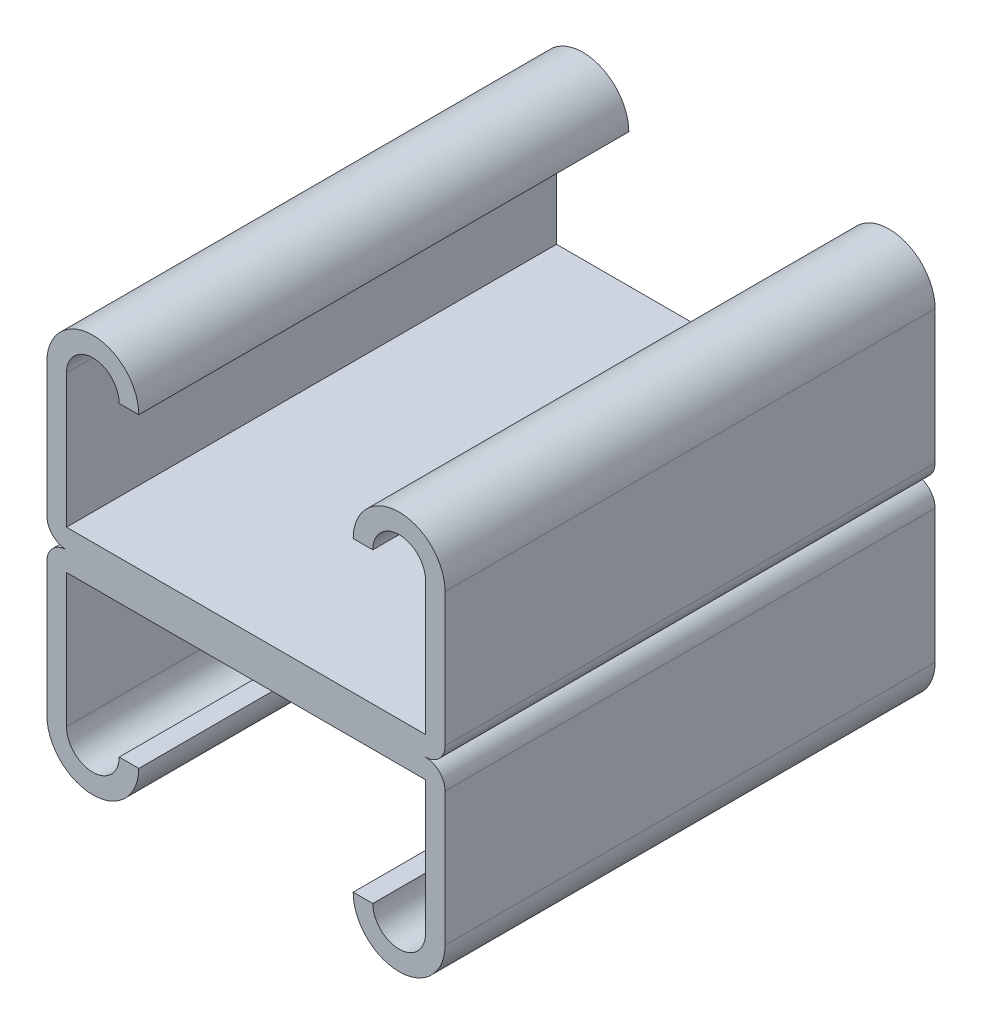
SolidWorks part; units mm, degrees
ref_plane "Plane1" through (0, 0, 0) normal (0, 0, 1) x (1, 0, 0)
ref_plane "Plane2" through (0, 0, 0) normal (0, 1, 0) x (1, 0, 0)
ref_plane "Plane3" through (0, 0, 0) normal (1, 0, 0) x (0, 0, -1)
sketch "Sketch1" plane through (0, 0, 0) normal (0, 0, 1) x (1, 0, 0)
  line L0 (-10.3188, 7.9375) -> (-10.3188, 1.016)
  line L1 (-9.3028, 0) -> (9.3028, 0)
  line L2 (10.3188, 1.016) -> (10.3187, 7.9375)
  line L3 (-6.5723, 7.9375) -> (-5.5563, 7.9375)
  line L4 (5.5562, 7.9375) -> (6.5722, 7.9375)
  line L6 (-9.3028, 7.9375) -> (-9.3028, 1.016)
  line L7 (-9.3028, 1.016) -> (9.3028, 1.016)
  line L8 (9.3028, 1.016) -> (9.3027, 7.9375)
  line L10 (-25.4, 10.3187) -> (25.4, 10.3187) construction
  arc A0 (10.3187, 7.9375) -> (5.5562, 7.9375) centre (7.9375, 7.9375) ccw
  arc A1 (-10.3188, 7.9375) -> (-5.5563, 7.9375) centre (-7.9375, 7.9375) cw
  arc A2 (-9.3028, 0) -> (-10.3188, 1.016) centre (-9.3028, 1.016) cw
  arc A3 (9.3028, 0) -> (10.3188, 1.016) centre (9.3028, 1.016) ccw
  arc A4 (-9.3028, 7.9375) -> (-6.5723, 7.9375) centre (-7.9375, 7.9375) cw
  arc A5 (9.3027, 7.9375) -> (6.5722, 7.9375) centre (7.9375, 7.9375) ccw
  dimension "D1" = 1.016
  dimension "Width" = 20.6375
  dimension "D2" = 10.3187
  dimension "D3" = 4.7625
  dimension "D4" = 11.1125
  dimension "D5" = 1.016
  dimension "D6" = 4.7625
  dimension "gauge" = 1.016
extrude "Base-Extrude" add sketch "Sketch1" along normal mid plane 25.4
mirror "Mirror1" about plane through (0, 0, 0) normal (0, 1, 0) of "Base-Extrude"
equation "\"D1@Sketch1\" = \"gauge@Sketch1\""
